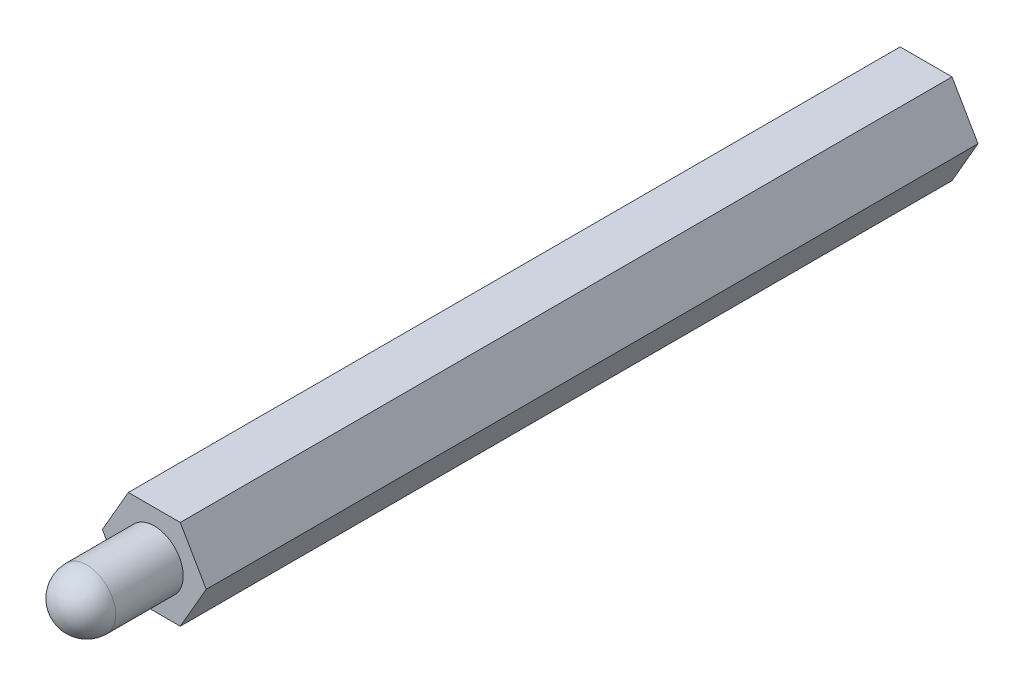
SolidWorks part; units mm, degrees
material "2A12"
ref_plane "前视基准面" through (0, 0, 0) normal (0, 0, 1) x (1, 0, 0)
ref_plane "上视基准面" through (0, 0, 0) normal (0, 1, 0) x (1, 0, 0)
ref_plane "右视基准面" through (0, 0, 0) normal (1, 0, 0) x (0, 0, -1)
sketch "草图1" plane through (0, 0, 0) normal (0, 0, 1) x (1, 0, 0)
  line L1 (2.6905, 0) -> (1.3452, 2.33)
  line L2 (1.3452, 2.33) -> (-1.3452, 2.33)
  line L3 (-1.3452, 2.33) -> (-2.6905, 0)
  line L4 (-2.6905, 0) -> (-1.3452, -2.33)
  line L5 (-1.3452, -2.33) -> (1.3452, -2.33)
  line L6 (1.3452, -2.33) -> (2.6905, 0)
  circle A0 centre (0, 0) radius 2.33 construction
  dimension "D1" = 4.66
extrude "凸台-拉伸1" add sketch "草图1" along normal blind 40
sketch "草图2" plane through (0, 0, 40) normal (0, 0, 1) x (1, 0, 0)
  circle A0 centre (0, 0) radius 1.5
  dimension "D1" = 3
extrude "凸台-拉伸2" add sketch "草图2" along normal blind 5
fillet "圆角1" radius 1.5 1 edges at (1.5, 0, 45)
